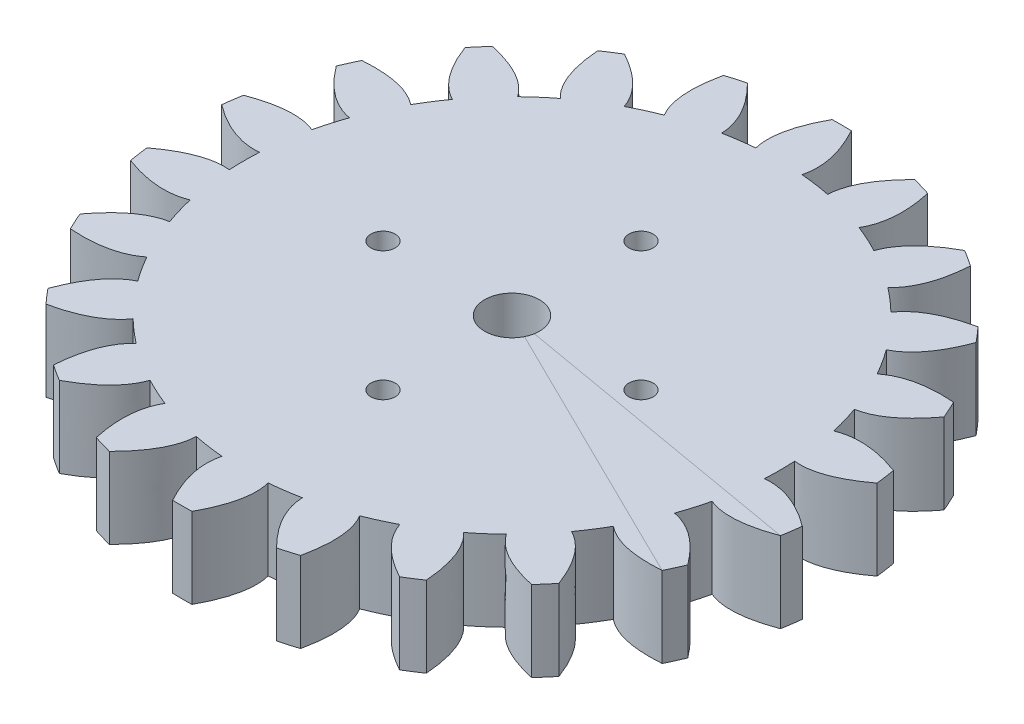
SolidWorks part; units mm, degrees
ref_plane "前视基准面" through (0, 0, 0) normal (0, 0, 1) x (1, 0, 0)
ref_plane "上视基准面" through (0, 0, 0) normal (0, 1, 0) x (1, 0, 0)
ref_plane "右视基准面" through (0, 0, 0) normal (1, 0, 0) x (0, 0, -1)
ref_plane "基准面1" through (0, 0, 0) normal (0, 0, -1) x (-1, 0, 0)
sketch "草图1" plane through (0, 0, 0) normal (0, 0, -1) x (-1, 0, 0)
  line L0 (-20.4545, -5) -> (0, -5)
  line L1 (0, -5) -> (0, 0)
  line L2 (0, 0) -> (-20.4545, 0)
  line L3 (-20.4545, 0) -> (-20.4545, -5)
  line L4 (0, -5) -> (0, 0) construction
  dimension "D1" = 20.4545
  dimension "D2" = 5
revolve "旋转1" add sketch "草图1" angle 360 about L4
sketch "草图2" plane through (0, 0, 0) normal (0, 1, 0) x (-1, 0, 0)
  arc A0 (-16.1851, 3.7743) -> (-15.6563, 5.5751) centre (0, 0) cw
  arc A1 (-18.8475, 7.9473) -> (-20.1522, 3.5041) centre (0, 0) ccw
  circle A2 centre (0, 0) radius 20.4545 construction
  ellipse E0 centre (-40.5548, -34.6982) end of major axis (-65.396, -72.9222) minor radius 11.5003 (-16.1851, 3.7743) -> (-20.1522, 3.5041) ccw
  ellipse E1 centre (-15.3576, 51.1155) end of major axis (-15.1254, 5.5293) minor radius 11.5003 (-18.8475, 7.9473) -> (-15.6563, 5.5751) ccw
  point P0 (-40.5548, -34.6982)
  point P1 (-50.1977, -28.4314)
  point P2 (-15.7137, 3.5259)
  point P3 (-16.1851, 3.7743)
  point P4 (-20.1522, 3.5041)
  point P5 (-18.1283, 4.0087)
  point P6 (-62.9813, -73.4051)
  point P16 (-15.3576, 51.1155)
  point P17 (-26.8578, 51.057)
  point P18 (-15.1254, 5.5293)
  point P19 (-18.8475, 7.9473)
  point P20 (-15.6563, 5.5751)
  point P21 (-17.4178, 6.4286)
  point P22 (-13.2974, 95.8025)
  dimension "D1" = 16.6193
  dimension "D2" = 20.4545
  dimension "D3" = 3.8574
  dimension "D4" = 13.2974
  dimension "D5" = 15.1254
  dimension "D6" = 15.3576
  dimension "D7" = 15.6563
  dimension "D8" = 15.7137
  dimension "D9" = 16.1851
  dimension "D10" = 18.8475
  dimension "D11" = 17.4178
  dimension "D12" = 18.1283
  dimension "D13" = 20.1522
  dimension "D14" = 30.9119
  dimension "D15" = 40.5548
  dimension "D16" = 3.5041
  dimension "D17" = 3.5259
  dimension "D19" = 62.9813
  dimension "D20" = 4.0087
  dimension "D23" = 6.4286
  dimension "D28" = 95.8025
  dimension "D34" = 73.4051
extrude "切除-拉伸1" cut sketch "草图2" against normal through all
sketch "草图3" plane through (0, 0, 0) normal (0, 1, 0) x (-1, 0, 0)
  arc A0 (-14.4661, 8.1813) -> (-13.4514, 9.7602) centre (0, 0) cw
  arc A1 (-15.8451, 12.9353) -> (-18.3487, 9.0396) centre (0, 0) ccw
  ellipse E0 centre (-48.6877, -21.867) end of major axis (-83.2915, -51.5442) minor radius 11.5003 (-14.4661, 8.1813) -> (-18.3487, 9.0396) ccw
  ellipse E1 centre (-0.3346, 53.3717) end of major axis (-12.9549, 9.5666) minor radius 11.5003 (-15.8451, 12.9353) -> (-13.4514, 9.7602) ccw
  point P0 (-48.6877, -21.867)
  point P1 (-83.2915, -51.5442)
  point P2 (-56.1744, -13.1374)
  point P3 (-14.4661, 8.1813)
  point P4 (-18.3487, 9.0396)
  point P5 (-16.2646, 8.9537)
  point P6 (-81.1107, -52.6878)
  point P16 (-0.3346, 53.3717)
  point P17 (-11.3855, 56.5555)
  point P18 (-12.9549, 9.5666)
  point P19 (-15.8451, 12.9353)
  point P20 (-13.4514, 9.7602)
  point P21 (-14.9011, 11.0753)
  point P22 (14.2319, 95.6682)
  dimension "D1" = 16.6193
  dimension "D2" = 20.4545
  dimension "D3" = 1.8035
  dimension "D4" = 3.8875
  dimension "D5" = 4.3071
  dimension "D6" = 5.251
  dimension "D7" = 5.6861
  dimension "D8" = 6.0684
  dimension "D9" = 6.7008
  dimension "D10" = 7.1972
  dimension "D11" = 8.7667
  dimension "D12" = 19.8175
  dimension "D13" = 20.1522
  dimension "D14" = 21.0487
  dimension "D15" = 28.5355
  dimension "D16" = 34.3841
  dimension "D17" = 4.306
  dimension "D19" = 5.4496
  dimension "D20" = 60.9585
  dimension "D24" = 7.5713
  dimension "D29" = 92.1641
  dimension "D36" = 56.1918
extrude "切除-拉伸2" cut sketch "草图3" against normal through all
sketch "草图28" plane through (0, 0, 0) normal (0, 1, 0) x (1, 0, 0)
  line L0 (20.1522, -3.5041) -> (0, 0)
  line L1 (0, 0) -> (18.3487, -9.0396)
  arc A0 (20.1522, -3.5041) -> (15.8451, -12.9353) centre (0, 0) ccw construction
  arc A1 (20.1522, -3.5041) -> (18.3487, -9.0396) centre (0, 0) ccw
  point P7 (18.3487, -9.0396)
extrude "切除-拉伸24" cut sketch "草图28" against normal blind 10
sketch "草图29" plane through (0, 0, 0) normal (0, 1, 0) x (1, 0, 0)
  line L2 (20.1522, -3.5041) -> (0, 0)
  line L3 (0, 0) -> (18.3487, -9.0396)
  arc A0 (13.4514, -9.7602) -> (14.4661, -8.1813) centre (0, 0) ccw
  arc A1 (15.0586, -13.8429) -> (15.8451, -12.9353) centre (0, 0) ccw
  arc A2 (18.3487, -9.0396) -> (18.8475, -7.9473) centre (0, 0) ccw
  arc A3 (15.6563, -5.5751) -> (16.1851, -3.7743) centre (0, 0) ccw
  arc A4 (18.3487, -9.0396) -> (18.8475, -7.9473) centre (0, 0) ccw
  arc A5 (15.6563, -5.5751) -> (16.1851, -3.7743) centre (0, 0) ccw
  arc A6 (10.1568, -13.1545) -> (11.5752, -11.9255) centre (0, 0) ccw
  arc A7 (10.5487, -17.5247) -> (11.5589, -16.8754) centre (0, 0) ccw
  arc A8 (6.0393, -15.4832) -> (7.7465, -14.7035) centre (0, 0) ccw
  arc A9 (5.1841, -19.7867) -> (6.3363, -19.4484) centre (0, 0) ccw
  arc A10 (1.4325, -16.5575) -> (3.2903, -16.2904) centre (0, 0) ccw
  arc A11 (-0.6004, -20.4457) -> (0.6004, -20.4457) centre (0, 0) ccw
  arc A12 (-3.2903, -16.2904) -> (-1.4325, -16.5575) centre (0, 0) ccw
  arc A13 (-6.3363, -19.4484) -> (-5.1841, -19.7867) centre (0, 0) ccw
  arc A14 (-7.7465, -14.7035) -> (-6.0393, -15.4832) centre (0, 0) ccw
  arc A15 (-11.5589, -16.8754) -> (-10.5487, -17.5247) centre (0, 0) ccw
  arc A16 (-11.5752, -11.9255) -> (-10.1568, -13.1545) centre (0, 0) ccw
  arc A17 (-15.8451, -12.9353) -> (-15.0586, -13.8429) centre (0, 0) ccw
  arc A18 (-14.4661, -8.1813) -> (-13.4514, -9.7602) centre (0, 0) ccw
  arc A19 (-18.8475, -7.9473) -> (-18.3487, -9.0396) centre (0, 0) ccw
  arc A20 (-16.1851, -3.7743) -> (-15.6563, -5.5751) centre (0, 0) ccw
  arc A21 (-20.3231, -2.3154) -> (-20.1522, -3.5041) centre (0, 0) ccw
  arc A22 (-16.5928, 0.9384) -> (-16.5928, -0.9384) centre (0, 0) ccw
  arc A23 (-20.1522, 3.5041) -> (-20.3231, 2.3154) centre (0, 0) ccw
  arc A24 (-15.6563, 5.5751) -> (-16.1851, 3.7743) centre (0, 0) ccw
  arc A25 (-18.3487, 9.0396) -> (-18.8475, 7.9473) centre (0, 0) ccw
  arc A26 (-13.4514, 9.7602) -> (-14.4661, 8.1813) centre (0, 0) ccw
  arc A27 (-15.0586, 13.8429) -> (-15.8451, 12.9353) centre (0, 0) ccw
  arc A28 (-10.1568, 13.1545) -> (-11.5752, 11.9255) centre (0, 0) ccw
  arc A29 (-10.5487, 17.5247) -> (-11.5589, 16.8754) centre (0, 0) ccw
  arc A30 (-6.0393, 15.4832) -> (-7.7465, 14.7035) centre (0, 0) ccw
  arc A31 (-5.1841, 19.7867) -> (-6.3363, 19.4484) centre (0, 0) ccw
  arc A32 (-1.4325, 16.5575) -> (-3.2903, 16.2904) centre (0, 0) ccw
  arc A33 (0.6004, 20.4457) -> (-0.6004, 20.4457) centre (0, 0) ccw
  arc A34 (3.2903, 16.2904) -> (1.4325, 16.5575) centre (0, 0) ccw
  arc A35 (6.3363, 19.4484) -> (5.1841, 19.7867) centre (0, 0) ccw
  arc A36 (7.7465, 14.7035) -> (6.0393, 15.4832) centre (0, 0) ccw
  arc A37 (11.5589, 16.8754) -> (10.5487, 17.5247) centre (0, 0) ccw
  arc A38 (11.5752, 11.9255) -> (10.1568, 13.1545) centre (0, 0) ccw
  arc A39 (15.8451, 12.9353) -> (15.0586, 13.8429) centre (0, 0) ccw
  arc A40 (14.4661, 8.1813) -> (13.4514, 9.7602) centre (0, 0) ccw
  arc A41 (18.8475, 7.9473) -> (18.3487, 9.0396) centre (0, 0) ccw
  arc A42 (16.1851, 3.7743) -> (15.6563, 5.5751) centre (0, 0) ccw
  arc A43 (20.3231, 2.3154) -> (20.1522, 3.5041) centre (0, 0) ccw
  arc A44 (16.5928, -0.9384) -> (16.5928, 0.9384) centre (0, 0) ccw
  arc A45 (20.1522, -3.5041) -> (20.3231, -2.3154) centre (0, 0) ccw
  ellipse E0 centre (48.6877, 21.867) end of major axis (14.0838, -7.8101) minor radius 11.5003 (14.4661, -8.1813) -> (18.3487, -9.0396) ccw
  ellipse E1 centre (0.3346, -53.3717) end of major axis (-12.2857, -97.1769) minor radius 11.5003 (15.8451, -12.9353) -> (13.4514, -9.7602) ccw
  ellipse E2 centre (15.3576, -51.1155) end of major axis (15.1254, -5.5293) minor radius 11.5003 (18.8475, -7.9473) -> (15.6563, -5.5751) ccw
  ellipse E3 centre (40.5548, 34.6982) end of major axis (65.396, 72.9222) minor radius 11.5003 (16.1851, -3.7743) -> (20.1522, -3.5041) ccw
  ellipse E4 centre (15.3576, -51.1155) end of major axis (15.1254, -5.5293) minor radius 11.5003 (18.8475, -7.9473) -> (15.6563, -5.5751) ccw
  ellipse E5 centre (40.5548, 34.6982) end of major axis (65.396, 72.9222) minor radius 11.5003 (16.1851, -3.7743) -> (20.1522, -3.5041) ccw
  ellipse E6 centre (52.8761, 7.2644) end of major axis (11.3129, -11.4616) minor radius 11.5003 (11.5752, -11.9255) -> (15.0586, -13.8429) ccw
  ellipse E7 centre (-14.7155, -51.3041) end of major axis (9.7349, -12.8289) minor radius 11.5003 (11.5589, -16.8754) -> (10.1568, -13.1545) ccw
  ellipse E8 centre (52.7809, -7.9268) end of major axis (7.6256, -14.1846) minor radius 11.5003 (7.7465, -14.7035) -> (10.5487, -17.5247) ccw
  ellipse E9 centre (-28.5734, -45.0801) end of major axis (5.7263, -15.0519) minor radius 11.5003 (6.3363, -19.4484) -> (6.0393, -15.4832) ccw
  ellipse E10 centre (48.4096, -22.4758) end of major axis (3.3204, -15.7583) minor radius 11.5003 (3.2903, -16.2904) -> (5.1841, -19.7867) ccw
  ellipse E11 centre (-40.1165, -35.204) end of major axis (1.2537, -16.0555) minor radius 11.5003 (0.6004, -20.4457) -> (1.4325, -16.5575) ccw
  ellipse E12 centre (40.1165, -35.204) end of major axis (81.4868, -54.3524) minor radius 11.5003 (-1.4325, -16.5575) -> (-0.6004, -20.4457) ccw
  ellipse E13 centre (-48.4096, -22.4758) end of major axis (-3.3204, -15.7583) minor radius 11.5003 (-5.1841, -19.7867) -> (-3.2903, -16.2904) ccw
  ellipse E14 centre (28.5734, -45.0801) end of major axis (-5.7263, -15.0519) minor radius 11.5003 (-6.0393, -15.4832) -> (-6.3363, -19.4484) ccw
  ellipse E15 centre (-52.7809, -7.9268) end of major axis (-7.6256, -14.1846) minor radius 11.5003 (-10.5487, -17.5247) -> (-7.7465, -14.7035) ccw
  ellipse E16 centre (14.7155, -51.3041) end of major axis (39.1659, -89.7792) minor radius 11.5003 (-10.1568, -13.1545) -> (-11.5589, -16.8754) ccw
  ellipse E17 centre (-52.8761, 7.2644) end of major axis (-11.3129, -11.4616) minor radius 11.5003 (-15.0586, -13.8429) -> (-11.5752, -11.9255) ccw
  ellipse E18 centre (-0.3346, -53.3717) end of major axis (-12.9549, -9.5666) minor radius 11.5003 (-13.4514, -9.7602) -> (-15.8451, -12.9353) ccw
  ellipse E19 centre (-48.6877, 21.867) end of major axis (-14.0838, -7.8101) minor radius 11.5003 (-18.3487, -9.0396) -> (-14.4661, -8.1813) ccw
  ellipse E20 centre (-15.3576, -51.1155) end of major axis (-15.1254, -5.5293) minor radius 11.5003 (-15.6563, -5.5751) -> (-18.8475, -7.9473) ccw
  ellipse E21 centre (-40.5548, 34.6982) end of major axis (-65.396, 72.9222) minor radius 11.5003 (-20.1522, -3.5041) -> (-16.1851, -3.7743) ccw
  ellipse E22 centre (-29.1365, -44.7183) end of major axis (-42.2024, -88.3925) minor radius 11.5003 (-16.5928, -0.9384) -> (-20.3231, -2.3154) ccw
  ellipse E23 centre (-29.1365, 44.7183) end of major axis (-42.2024, 88.3925) minor radius 11.5003 (-20.3231, 2.3154) -> (-16.5928, 0.9384) ccw
  ellipse E24 centre (-40.5548, -34.6982) end of major axis (-15.7137, 3.5259) minor radius 11.5003 (-16.1851, 3.7743) -> (-20.1522, 3.5041) ccw
  ellipse E25 centre (-15.3576, 51.1155) end of major axis (-15.1254, 5.5293) minor radius 11.5003 (-18.8475, 7.9473) -> (-15.6563, 5.5751) ccw
  ellipse E26 centre (-48.6877, -21.867) end of major axis (-14.0838, 7.8101) minor radius 11.5003 (-14.4661, 8.1813) -> (-18.3487, 9.0396) ccw
  ellipse E27 centre (-0.3346, 53.3717) end of major axis (-12.9549, 9.5666) minor radius 11.5003 (-15.8451, 12.9353) -> (-13.4514, 9.7602) ccw
  ellipse E28 centre (-52.8761, -7.2644) end of major axis (-11.3129, 11.4616) minor radius 11.5003 (-11.5752, 11.9255) -> (-15.0586, 13.8429) ccw
  ellipse E29 centre (14.7155, 51.3041) end of major axis (39.1659, 89.7792) minor radius 11.5003 (-11.5589, 16.8754) -> (-10.1568, 13.1545) ccw
  ellipse E30 centre (-52.7809, 7.9268) end of major axis (-7.6256, 14.1846) minor radius 11.5003 (-7.7465, 14.7035) -> (-10.5487, 17.5247) ccw
  ellipse E31 centre (28.5734, 45.0801) end of major axis (-5.7263, 15.0519) minor radius 11.5003 (-6.3363, 19.4484) -> (-6.0393, 15.4832) ccw
  ellipse E32 centre (-48.4096, 22.4758) end of major axis (-3.3204, 15.7583) minor radius 11.5003 (-3.2903, 16.2904) -> (-5.1841, 19.7867) ccw
  ellipse E33 centre (40.1165, 35.204) end of major axis (-1.2537, 16.0555) minor radius 11.5003 (-0.6004, 20.4457) -> (-1.4325, 16.5575) ccw
  ellipse E34 centre (-40.1165, 35.204) end of major axis (-81.4868, 54.3524) minor radius 11.5003 (1.4325, 16.5575) -> (0.6004, 20.4457) ccw
  ellipse E35 centre (48.4096, 22.4758) end of major axis (3.3204, 15.7583) minor radius 11.5003 (5.1841, 19.7867) -> (3.2903, 16.2904) ccw
  ellipse E36 centre (-28.5734, 45.0801) end of major axis (5.7263, 15.0519) minor radius 11.5003 (6.0393, 15.4832) -> (6.3363, 19.4484) ccw
  ellipse E37 centre (52.7809, 7.9268) end of major axis (7.6256, 14.1846) minor radius 11.5003 (10.5487, 17.5247) -> (7.7465, 14.7035) ccw
  ellipse E38 centre (-14.7155, 51.3041) end of major axis (9.7349, 12.8289) minor radius 11.5003 (10.1568, 13.1545) -> (11.5589, 16.8754) ccw
  ellipse E39 centre (52.8761, -7.2644) end of major axis (11.3129, 11.4616) minor radius 11.5003 (15.0586, 13.8429) -> (11.5752, 11.9255) ccw
  ellipse E40 centre (0.3346, 53.3717) end of major axis (12.9549, 9.5666) minor radius 11.5003 (13.4514, 9.7602) -> (15.8451, 12.9353) ccw
  ellipse E41 centre (48.6877, -21.867) end of major axis (83.2915, -51.5442) minor radius 11.5003 (18.3487, 9.0396) -> (14.4661, 8.1813) ccw
  ellipse E42 centre (15.3576, 51.1155) end of major axis (15.5899, 96.7018) minor radius 11.5003 (15.6563, 5.5751) -> (18.8475, 7.9473) ccw
  ellipse E43 centre (40.5548, -34.6982) end of major axis (65.396, -72.9222) minor radius 11.5003 (20.1522, 3.5041) -> (16.1851, 3.7743) ccw
  ellipse E44 centre (29.1365, 44.7183) end of major axis (16.0705, 1.044) minor radius 11.5003 (16.5928, 0.9384) -> (20.3231, 2.3154) ccw
  ellipse E45 centre (29.1365, -44.7183) end of major axis (16.0705, -1.044) minor radius 11.5003 (20.3231, -2.3154) -> (16.5928, -0.9384) ccw
  point P1 (0, 0)
  point P344 (0, 0)
  dimension "D1" = 0
  dimension "D2" = 22
extrude "凸台-拉伸1" add sketch "草图29" against normal up to surface (5 mm away) from surface at 0 separate body contours A45 E45 A44 E44 A43 E43 A42 E42 A41 E41 A40 E40 A39 E39 A38 E38 A37 E37 A36 E36 A35 E35 A34 E34 A33 E33 A32 E32 A31 E31 A30 E30 A29 E29 A28 E28 A27 E27 A26 E26 A25 E25 A24 E24 A23 E23 A22 E22 A21 E21 A20
sketch "草图30" plane through (0, -5, 0) normal (0, -1, 0) x (1, 0, 0)
  circle A0 centre (0, 0) radius 10.5
extrude "切除-拉伸26" cut sketch "草图30" against normal blind 2.5
sketch "草图31" plane through (0, -2.5, 0) normal (0, -1, 0) x (1, 0, 0)
  circle A0 centre (0, 8) radius 0.75
  circle A1 centre (8, 0) radius 0.75
  circle A2 centre (0, -8) radius 0.75
  circle A3 centre (-8, 0) radius 0.75
  circle A4 centre (0, 0) radius 1.7
  point P11 (0, 0)
  dimension "D1" = 4
extrude "切除-拉伸27" cut sketch "草图31" against normal up to next (2.5 mm away)
sketch "草图32" plane through (0, -2.5, 0) normal (0, -1, 0) x (1, 0, 0)
  line L2 (0, 0) -> (10.3448, 1.7987)
  line L3 (9.419, 4.6403) -> (0, 0)
  line L4 (0, 0) -> (1.6749, 0.2912)
  line L5 (1.525, 0.7513) -> (0, 0)
  arc A1 (10.3448, 1.7987) -> (9.419, 4.6403) centre (0, 0) ccw
  arc A2 (10.3448, 1.7987) -> (9.419, 4.6403) centre (0, 0) ccw
  arc A4 (1.6749, 0.2912) -> (1.525, 0.7513) centre (0, 0) ccw
  line M4 (0, 0) -> (10.3448, 1.7987)
  line M6 (9.419, 4.6403) -> (0, 0)
  dimension "D1" = 0
extrude "切除-拉伸28" cut sketch "草图32" against normal blind 3 contours A4 M4 M6
